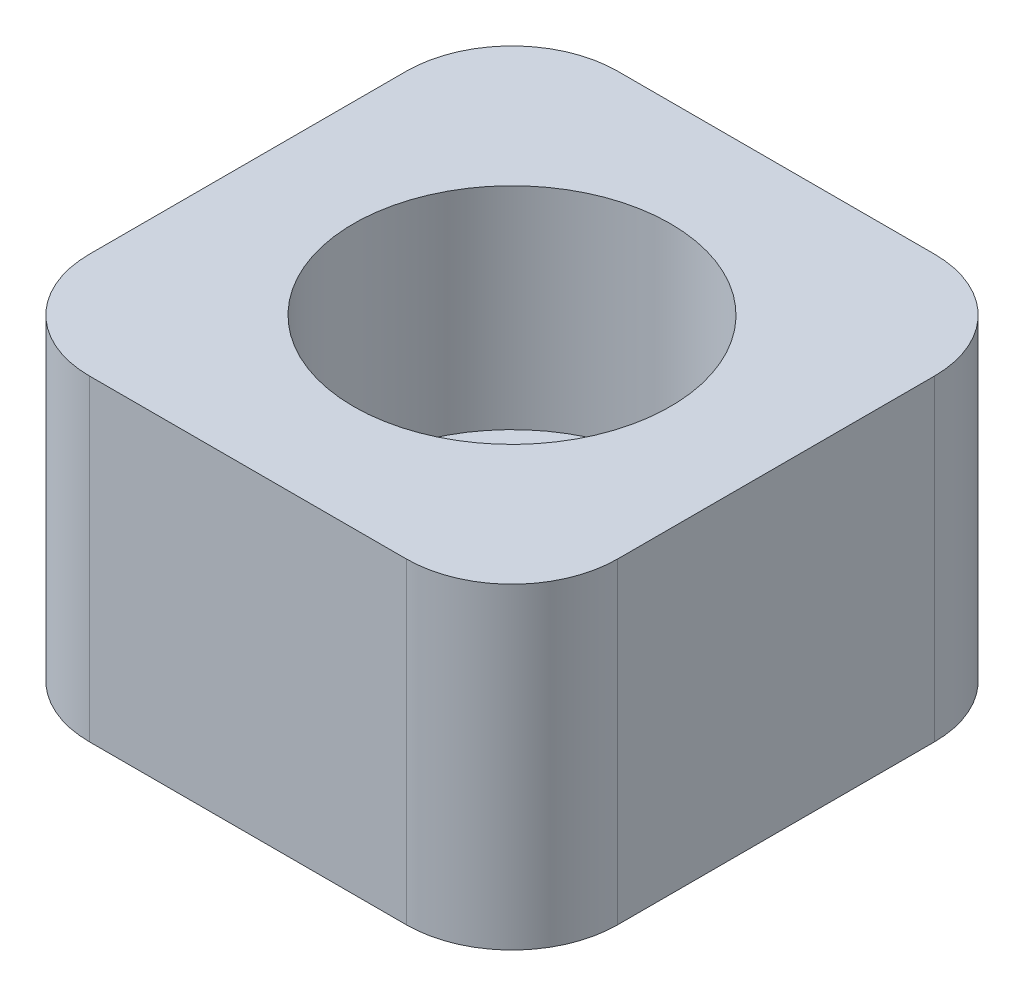
SolidWorks part; units mm, degrees
ref_plane "Front Plane" through (0, 0, 0) normal (0, 0, 1) x (1, 0, 0)
ref_plane "Top Plane" through (0, 0, 0) normal (0, 1, 0) x (1, 0, 0)
ref_plane "Right Plane" through (0, 0, 0) normal (1, 0, 0) x (0, 0, -1)
sketch "Sketch1" plane through (0, 0, 0) normal (0, 1, 0) x (1, 0, 0)
  line L1 (-25, -25) -> (25, -25)
  line L2 (-25, -25) -> (-25, 25)
  line L3 (-25, 25) -> (25, 25)
  line L4 (25, -25) -> (25, 25)
  line L5 (-25, -25) -> (25, 25) construction
  line L6 (-25, 25) -> (25, -25) construction
  point P0 (0, 0)
  dimension "D1" = 50
  dimension "D2" = 50
extrude "Boss-Extrude1" add sketch "Sketch1" along normal blind 30
sketch "Sketch2" plane through (0, 30, 0) normal (0, 1, 0) x (1, 0, 0)
  circle A0 centre (0, 0) radius 15
extrude "Cut-Extrude1" cut sketch "Sketch2" against normal blind 20
fillet "Fillet1" radius 10 4 edges at (-25, 15, 25) (25, 15, 25) (25, 15, -25) (-25, 15, -25)
sketch "Sketch3" plane through (0, 0, 0) normal (0, -1, 0) x (1, 0, 0)
  circle A0 centre (15, -15) radius 3
  circle A1 centre (-15, -15) radius 3
  circle A2 centre (-15, 15) radius 3
  circle A3 centre (15, 15) radius 3
extrude "Cut-Extrude2" cut sketch "Sketch3" against normal blind 10
